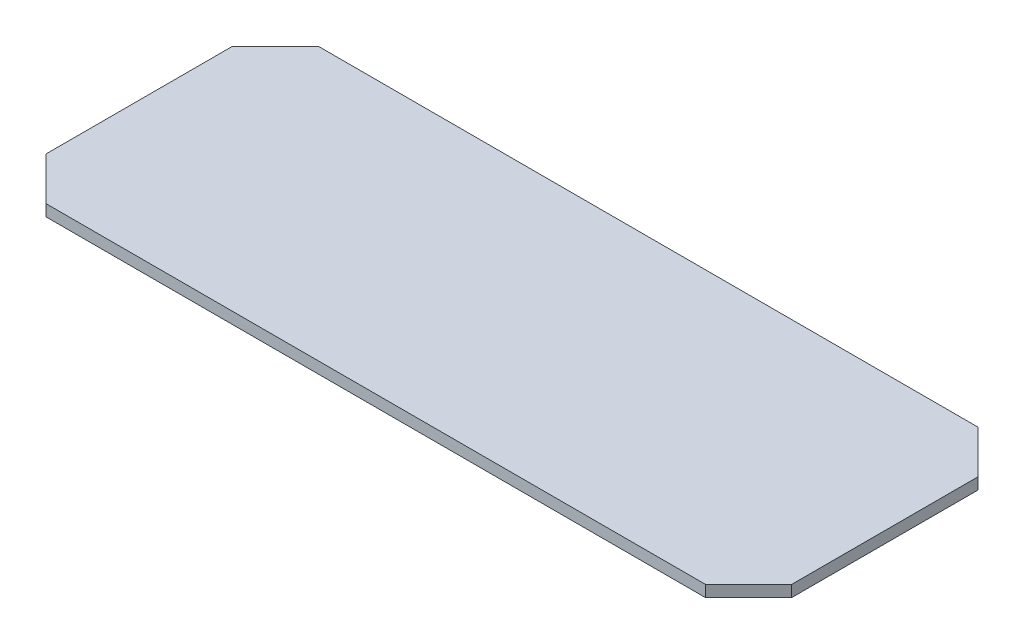
SolidWorks part; units mm, degrees
ref_plane "Front" through (0, 0, 0) normal (0, 0, 1) x (1, 0, 0)
ref_plane "Top" through (0, 0, 0) normal (0, 1, 0) x (1, 0, 0)
ref_plane "Right" through (0, 0, 0) normal (1, 0, 0) x (0, 0, -1)
sketch "草图1" plane through (0, 0, 0) normal (0, 1, 0) x (1, 0, 0)
  line L1 (65, -23.75) -> (-65, -23.75)
  line L2 (65, -23.75) -> (65, 23.75)
  line L3 (65, 23.75) -> (-65, 23.75)
  line L4 (-65, -23.75) -> (-65, 23.75)
  line L5 (65, -23.75) -> (-65, 23.75) construction
  line L6 (65, 23.75) -> (-65, -23.75) construction
  point P0 (0, 0)
  dimension "D1" = 130
  dimension "D2" = 47.5
extrude "凸台-拉伸1" add sketch "草图1" along normal blind 2
chamfer "倒角1" distance 7.5 angle 45 4 edges at (-65, 1, -23.75) (-65, 1, 23.75) (65, 1, -23.75) (65, 1, 23.75)
